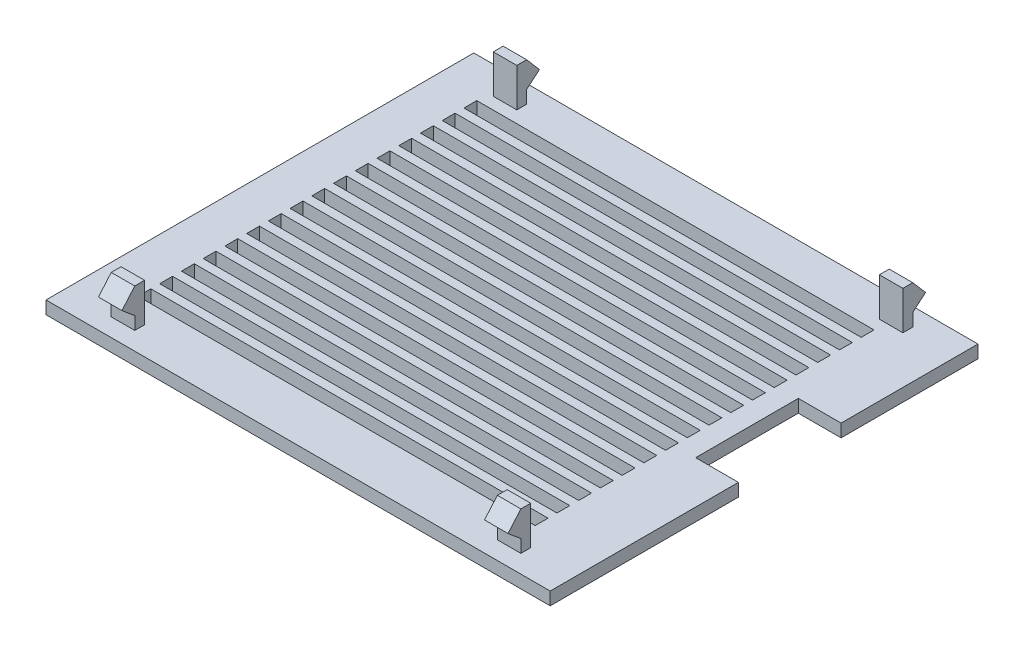
SolidWorks part; units mm, degrees
ref_plane "Front Plane" through (0, 0, 0) normal (0, 0, 1) x (1, 0, 0)
ref_plane "Top Plane" through (0, 0, 0) normal (0, 1, 0) x (1, 0, 0)
ref_plane "Right Plane" through (0, 0, 0) normal (1, 0, 0) x (0, 0, -1)
sketch "Sketch1" plane through (0, 0, 0) normal (0, 1, 0) x (1, 0, 0)
  line L1 (0, 0) -> (117.85, 0)
  line L2 (0, 0) -> (0, 100)
  line L3 (0, 100) -> (117.85, 100)
  line L4 (117.85, 0) -> (117.85, 100)
  dimension "D1" = 100
  dimension "D2" = 117.85
extrude "Boss-Extrude1" add sketch "Sketch1" along normal blind 3
sketch "Sketch2" plane through (117.85, 0, 0) normal (1, 0, 0) x (0, 0, -1)
  line L0 (4.2, 3) -> (4.2, 6)
  line L1 (0, 3) -> (100, 3) construction
  line L2 (4.2, 6) -> (1.2, 8.5173)
  line L3 (1.2, 8.5173) -> (4.2, 12)
  line L4 (4.2, 12) -> (4.2, 6)
  line L5 (0, 3) -> (0, 0) construction
  line L6 (4.2, 12) -> (6.5, 12)
  line L7 (6.5, 12) -> (6.5, 3)
  line L8 (6.5, 3) -> (4.2, 3)
  line M7 (100, 3) -> (0, 3)
  dimension "D1" = 130
  dimension "D2" = 6
  dimension "D3" = 3
  dimension "D4" = 4.2
  dimension "D5" = 2.3
  dimension "D6" = 3
extrude "Boss-Extrude2" add sketch "Sketch2" against normal up to surface (117.85 mm away) contours L7 L6 L4 L0 M7 | L4 L3 L2 up to face at (0, 1.5, -50)
sketch "Sketch3" plane through (0, 0, 0) normal (0, -1, 0) x (1, 0, 0)
  line L0 (117.85, -44) -> (107.85, -44)
  line L1 (117.85, 0) -> (117.85, -100) construction
  line L2 (107.85, -44) -> (107.85, -68)
  line L3 (107.85, -68) -> (117.85, -68)
  line L6 (0, 0) -> (117.85, 0) construction
  line L7 (117.85, -68) -> (117.85, -44)
  dimension "D1" = 24
  dimension "D2" = 10
  dimension "D3" = 68
extrude "Cut-Extrude1" cut sketch "Sketch3" against normal up to surface (3 mm away) up to face at (58.925, 3, -53.25)
ref_plane "Plane1" through (0, 0, -50) normal (0, 0, 1) x (1, 0, 0)
mirror "Mirror1" about plane through (0, 0, -50) normal (0, 0, 1) of "Boss-Extrude2"
sketch "Sketch4" plane through (0, 0, -50) normal (0, 0, 1) x (1, 0, 0)
  line L0 (0, 12) -> (117.85, 12) construction
  line L1 (0, 3) -> (11.05, 3)
  line L2 (0, 3) -> (0, 12)
  line L3 (0, 12) -> (11.05, 12)
  line L4 (11.05, 3) -> (11.05, 12)
  line L5 (0, 3) -> (117.85, 3) construction
  line L6 (117.85, 3) -> (106.8, 3)
  line L7 (117.85, 3) -> (117.85, 12)
  line L8 (117.85, 12) -> (106.8, 12)
  line L9 (106.8, 3) -> (106.8, 12)
  line L10 (16.55, 12) -> (101.3, 12)
  line L11 (16.55, 12) -> (16.55, 3)
  line L12 (16.55, 3) -> (101.3, 3)
  line L13 (101.3, 12) -> (101.3, 3)
  dimension "D1" = 11.05
  dimension "D2" = 11.05
  dimension "D3" = 5.5
  dimension "D4" = 5.5
extrude "Cut-Extrude2" cut sketch "Sketch4" against normal through all both and the other way through all contours L11 L10 L13 L12 | L2 L1 L4 L3 | L7 L6 L9 L8
sketch "Sketch5" plane through (0, 0, 0) normal (0, -1, 0) x (-1, 0, 0)
  line L0 (-11.05, 6.5) -> (-16.55, 6.5) construction
  line L1 (-10, 11.5) -> (-102.85, 11.5)
  line L2 (-10, 11.5) -> (-10, 14.5)
  line L3 (-10, 14.5) -> (-102.85, 14.5)
  line L4 (-102.85, 11.5) -> (-102.85, 14.5)
  line L6 (0, 100) -> (0, 0) construction
  line L7 (-107.85, 44) -> (-107.85, 68) construction
  line L8 (-10, 16.58) -> (-10, 19.58)
  line L9 (-10, 16.58) -> (-102.85, 16.58)
  line L10 (-102.85, 16.58) -> (-102.85, 19.58)
  line L11 (-10, 19.58) -> (-102.85, 19.58)
  line L12 (-10, 21.66) -> (-10, 24.66)
  line L13 (-10, 21.66) -> (-102.85, 21.66)
  line L14 (-102.85, 21.66) -> (-102.85, 24.66)
  line L15 (-10, 24.66) -> (-102.85, 24.66)
  line L16 (-10, 26.74) -> (-10, 29.74)
  line L17 (-10, 26.74) -> (-102.85, 26.74)
  line L18 (-102.85, 26.74) -> (-102.85, 29.74)
  line L19 (-10, 29.74) -> (-102.85, 29.74)
  line L20 (-10, 31.82) -> (-10, 34.82)
  line L21 (-10, 31.82) -> (-102.85, 31.82)
  line L22 (-102.85, 31.82) -> (-102.85, 34.82)
  line L23 (-10, 34.82) -> (-102.85, 34.82)
  line L24 (-10, 36.9) -> (-10, 39.9)
  line L25 (-10, 36.9) -> (-102.85, 36.9)
  line L26 (-102.85, 36.9) -> (-102.85, 39.9)
  line L27 (-10, 39.9) -> (-102.85, 39.9)
  line L28 (-10, 41.98) -> (-10, 44.98)
  line L29 (-10, 41.98) -> (-102.85, 41.98)
  line L30 (-102.85, 41.98) -> (-102.85, 44.98)
  line L31 (-10, 44.98) -> (-102.85, 44.98)
  line L32 (-10, 47.06) -> (-10, 50.06)
  line L33 (-10, 47.06) -> (-102.85, 47.06)
  line L34 (-102.85, 47.06) -> (-102.85, 50.06)
  line L35 (-10, 50.06) -> (-102.85, 50.06)
  line L36 (-10, 52.14) -> (-10, 55.14)
  line L37 (-10, 52.14) -> (-102.85, 52.14)
  line L38 (-102.85, 52.14) -> (-102.85, 55.14)
  line L39 (-10, 55.14) -> (-102.85, 55.14)
  line L40 (-10, 57.22) -> (-10, 60.22)
  line L41 (-10, 57.22) -> (-102.85, 57.22)
  line L42 (-102.85, 57.22) -> (-102.85, 60.22)
  line L43 (-10, 60.22) -> (-102.85, 60.22)
  line L44 (-10, 62.3) -> (-10, 65.3)
  line L45 (-10, 62.3) -> (-102.85, 62.3)
  line L46 (-102.85, 62.3) -> (-102.85, 65.3)
  line L47 (-10, 65.3) -> (-102.85, 65.3)
  line L48 (-10, 67.38) -> (-10, 70.38)
  line L49 (-10, 67.38) -> (-102.85, 67.38)
  line L50 (-102.85, 67.38) -> (-102.85, 70.38)
  line L51 (-10, 70.38) -> (-102.85, 70.38)
  line L52 (-10, 72.46) -> (-10, 75.46)
  line L53 (-10, 72.46) -> (-102.85, 72.46)
  line L54 (-102.85, 72.46) -> (-102.85, 75.46)
  line L55 (-10, 75.46) -> (-102.85, 75.46)
  line L56 (-10, 77.54) -> (-10, 80.54)
  line L57 (-10, 77.54) -> (-102.85, 77.54)
  line L58 (-102.85, 77.54) -> (-102.85, 80.54)
  line L59 (-10, 80.54) -> (-102.85, 80.54)
  line L60 (-10, 82.62) -> (-10, 85.62)
  line L61 (-10, 82.62) -> (-102.85, 82.62)
  line L62 (-102.85, 82.62) -> (-102.85, 85.62)
  line L63 (-10, 85.62) -> (-102.85, 85.62)
  line L64 (-10, 87.7) -> (-10, 90.7)
  line L65 (-10, 87.7) -> (-102.85, 87.7)
  line L66 (-102.85, 87.7) -> (-102.85, 90.7)
  line L67 (-10, 90.7) -> (-102.85, 90.7)
  dimension "D1" = 5
  dimension "D2" = 5
  dimension "D3" = 10
  dimension "D4" = 3
  dimension "D6" = 2.08
  dimension "D5" = 16
extrude "Cut-Extrude3" cut sketch "Sketch5" against normal up to surface (3 mm away) up to face at (104.05, 3, -94.65)
